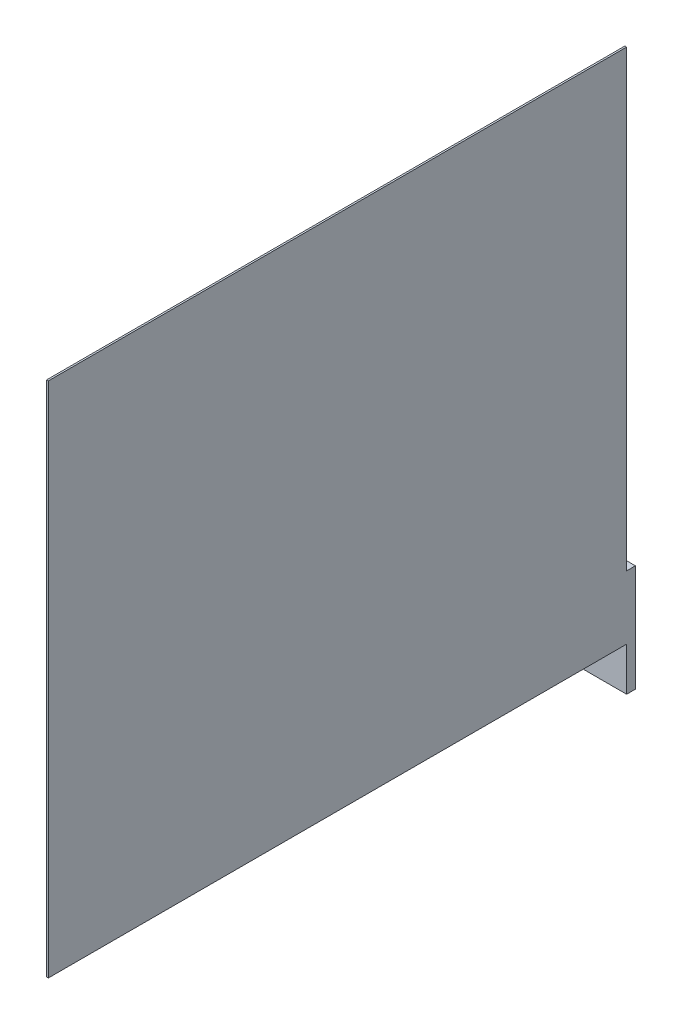
SolidWorks part; units mm, degrees
ref_plane "前视基准面" through (0, 0, 0) normal (0, 0, 1) x (1, 0, 0)
ref_plane "上视基准面" through (0, 0, 0) normal (0, 1, 0) x (1, 0, 0)
ref_plane "右视基准面" through (0, 0, 0) normal (1, 0, 0) x (0, 0, -1)
other "Configuration Table"
sketch "草图1" plane through (0, 0, 0) normal (0, 0, 1) x (1, 0, 0)
  line L0 (-112.6412, -73.6485) -> (-112.6412, -49.2485)
  line L1 (-112.6412, -73.6485) -> (-88.2675, -73.6485)
  line L2 (-112.6412, -49.2485) -> (-88.2675, -49.2485)
  line L3 (-88.2675, -73.6485) -> (-88.2675, -49.2485)
extrude "凸台-拉伸1" add sketch "草图1" along normal blind 2
sketch "草图2" plane through (0, 0, 2) normal (0, 0, 1) x (1, 0, 0)
  line L0 (-88.2675, -63.7379) -> (-88.2675, 54.3057)
  line L1 (-88.2675, -63.7379) -> (-88.6668, -63.7379)
  line L2 (-88.2675, 54.3057) -> (-88.6668, 54.3057)
  line L3 (-88.6668, -63.7379) -> (-88.6668, 54.3057)
  line L5 (-88.2675, -73.6485) -> (-88.2675, -49.2485) construction
extrude "凸台-拉伸2" add sketch "草图2" along normal blind 132
fillet "圆角1" radius 10 1 edges at (-88.6668, -56.4932, 2)
